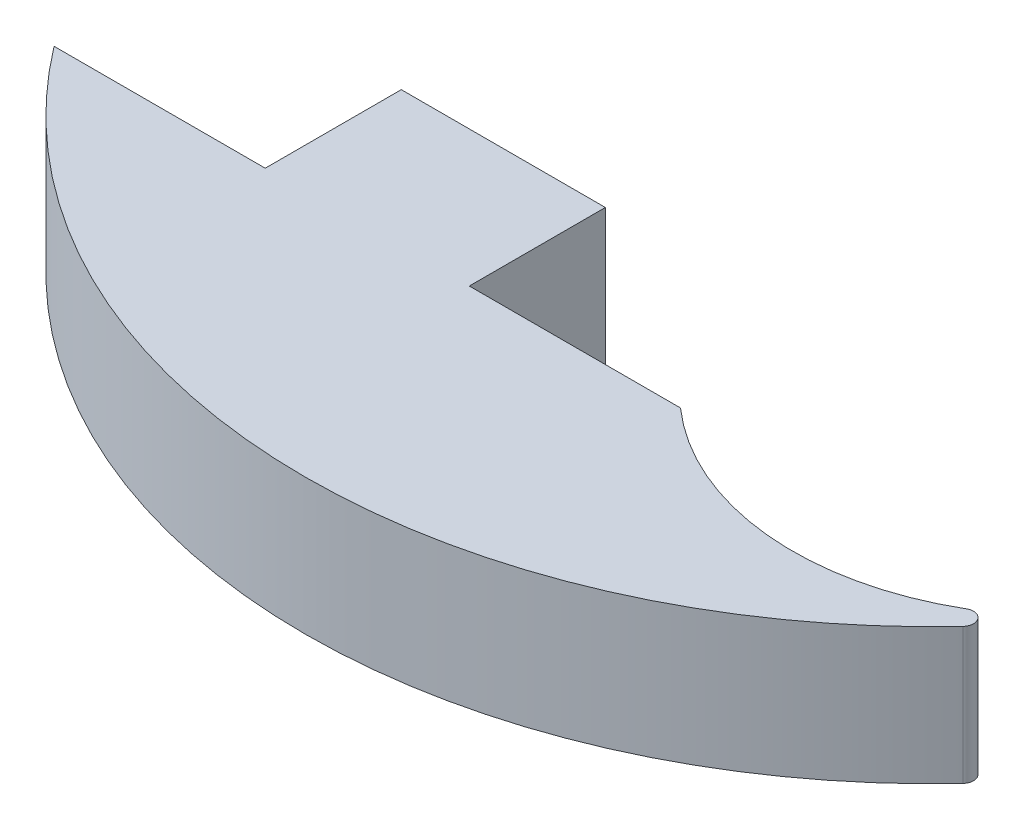
SolidWorks part; units mm, degrees
material "AISI 4130 Steel, annealed at 865C"
ref_plane "X-Y Datum" through (0, 0, 0) normal (0, 0, 1) x (1, 0, 0)
ref_plane "X-Z Datum" through (0, 0, 0) normal (0, 1, 0) x (1, 0, 0)
ref_plane "Y-Z Datum" through (0, 0, 0) normal (1, 0, 0) x (0, 0, -1)
sketch "Sketch1" plane through (0, 0, 0) normal (0, 1, 0) x (1, 0, 0)
  line L0 (-50.9024, -40.0059) -> (-57.5024, -40.0059) construction
  line L1 (-66.9024, -43.1809) -> (-24.9655, -43.1809)
  line L2 (-54.2024, -41.3694) -> (-54.2024, -38.6423) construction
  line L5 (-41.5024, -43.1809) -> (-66.9024, -43.1809)
  line L6 (-54.2024, -43.1809) -> (-54.2024, -48.3956) construction
  line L7 (-66.9024, -36.8309) -> (-66.9024, -43.1809)
  circle A3 centre (-16.5652, -33.6559) radius 12.7
  circle A5 centre (-16.5652, -33.6559) radius 12.7
  arc A6 (-5.5128, -39.9115) -> (-54.2024, -43.1809) centre (-30.9335, -25.5236) cw
  point P3 (-54.2024, -40.0059)
  point P11 (-15.8357, -44.7684)
  point P16 (-54.2024, -40.0059)
  dimension "D1" = 12.7
  dimension "D2" = 29.21
extrude "Boss-Extrude1" add sketch "Sketch1" along normal mid plane 6.35
sketch "Sketch2" plane through (0, 3.175, 0) normal (0, 1, 0) x (1, 0, 0)
  line L0 (-54.2024, -43.1809) -> (-24.9655, -43.1809) construction
  line L1 (-54.2024, -43.1809) -> (-24.9655, -43.1809)
  line L2 (-39.584, -43.1809) -> (-39.584, -36.8309) construction
  line L8 (-34.8215, -43.1809) -> (-44.3465, -43.1809)
  line L9 (-34.8215, -43.1809) -> (-34.8215, -36.8309)
  line L10 (-34.8215, -36.8309) -> (-44.3465, -36.8309)
  line L11 (-44.3465, -43.1809) -> (-44.3465, -36.8309)
  line L12 (-34.8215, -43.1809) -> (-44.3465, -36.8309) construction
  line L13 (-34.8215, -36.8309) -> (-44.3465, -43.1809) construction
  point P2 (-39.584, -40.0059)
  dimension "D1" = 6.35
  dimension "D2" = 9.525
extrude "Boss-Extrude2" add sketch "Sketch2" against normal blind 6.35 contours L11 L1 L9 L10
sketch "Sketch3" plane through (0, 3.175, 0) normal (0, 1, 0) x (1, 0, 0)
  line L5 (-24.9655, -43.1809) -> (-34.8215, -43.1809)
  line L6 (-34.8215, -43.1809) -> (-34.8215, -36.8309)
  line L7 (-34.8215, -36.8309) -> (-44.3465, -36.8309)
  line L8 (-44.3465, -36.8309) -> (-44.3465, -43.1809)
  line L9 (-44.3465, -43.1809) -> (-54.2024, -43.1809)
  line L10 (-24.9655, -43.1809) -> (-34.8215, -43.1809)
  line L11 (-34.8215, -43.1809) -> (-34.8215, -36.8309)
  line L12 (-34.8215, -36.8309) -> (-44.3465, -36.8309)
  line L13 (-44.3465, -36.8309) -> (-44.3465, -43.1809)
  line L14 (-44.3465, -43.1809) -> (-54.2024, -43.1809)
  arc A0 (-10.1676, -44.6267) -> (-9.5396, -45.4114) centre (-9.9117, -45.0656) cw
  arc A2 (-54.2024, -43.1809) -> (-5.5128, -39.9115) centre (-30.9335, -25.5236) ccw
  arc A3 (-24.9655, -43.1809) -> (-5.5128, -39.9115) centre (-16.5652, -33.6559) ccw
  arc A4 (-54.2024, -43.1809) -> (-9.5396, -45.4114) centre (-30.9335, -25.5236) ccw
  arc A5 (-24.9655, -43.1809) -> (-10.1676, -44.6267) centre (-16.5652, -33.6559) ccw
  arc M9 (-54.2024, -43.1809) -> (-5.5128, -39.9115) centre (-30.9335, -25.5236) ccw
  arc M10 (-5.5128, -39.9115) -> (-24.9655, -43.1809) centre (-16.5652, -33.6559) cw
  dimension "D2" = 0.508
  dimension "D1" = 0
extrude "Cut-Extrude1" cut sketch "Sketch3" against normal through all contours A0 M10 M9
